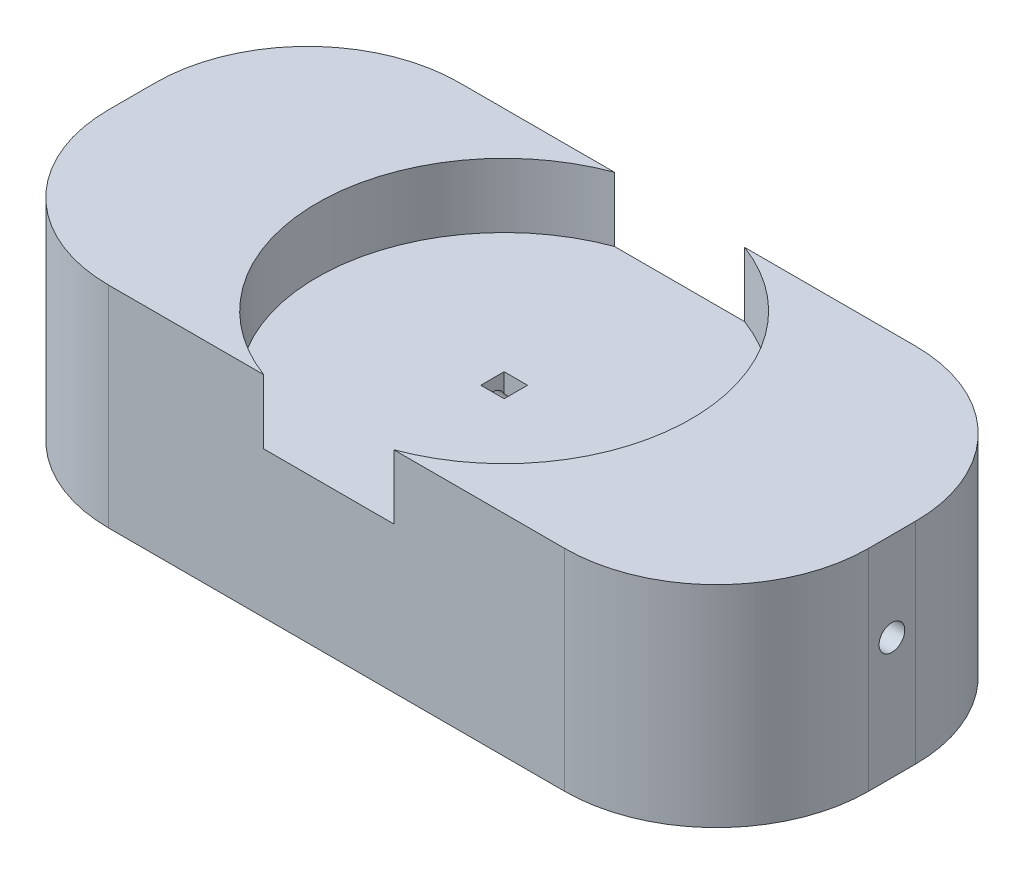
SolidWorks part; units mm, degrees
ref_plane "Front Plane" through (0, 0, 0) normal (0, 0, 1) x (1, 0, 0)
ref_plane "Top Plane" through (0, 0, 0) normal (0, 1, 0) x (1, 0, 0)
ref_plane "Right Plane" through (0, 0, 0) normal (1, 0, 0) x (0, 0, -1)
sketch "Sketch1" plane through (0, 0, 0) normal (0, 1, 0) x (1, 0, 0)
  line L1 (-25, -15) -> (40, -15)
  line L2 (-25, -15) -> (-25, 15)
  line L3 (-25, 15) -> (40, 15)
  line L4 (40, -15) -> (40, 15)
  line L5 (-25, -15) -> (40, 15) construction
  line L6 (-25, 15) -> (40, -15) construction
  point P0 (0, 0)
  dimension "D1" = 30
  dimension "D2" = 65
extrude "Boss-Extrude1" add sketch "Sketch1" along normal blind 58
sketch "Sketch3" plane through (-25, 0, 0) normal (-1, 0, 0) x (0, 0, 1)
  line L0 (-15, 58) -> (15, 58) construction
  circle A0 centre (0, 50.4) radius 1.1
  dimension "D1" = 2.2
  dimension "D2" = 7.6
fillet "Fillet1" radius 13 4 edges at (40, 29, -15) (-25, 29, -15) (40, 29, 15) (-25, 29, 15)
ref_plane "Plane2" through (0, -10, 0) normal (0, -1, 0) x (-1, 0, 0)
sketch "Sketch15" plane through (0, -10, 0) normal (0, -1, 0) x (-1, 0, 0)
  line L1 (-41.9055, 15.8797) -> (41.7906, 15.8797)
  line L2 (-41.9055, 15.8797) -> (-41.9055, -15.8187)
  line L3 (-41.9055, -15.8187) -> (41.7906, -15.8187)
  line L4 (41.7906, 15.8797) -> (41.7906, -15.8187)
extrude "Cut-Extrude7" cut sketch "Sketch15" against normal blind 50
ref_plane "Plane3" through (0, 40, 0) normal (0, -1, 0) x (-1, 0, 0)
ref_plane "Plane4" through (0, 58, 0) normal (0, 1, 0) x (1, 0, 0)
sketch "Sketch18" plane through (0, 58, 0) normal (0, 1, 0) x (1, 0, 0)
  circle A0 centre (6.8285, 0) radius 16
  dimension "D1" = 32
extrude "Cut-Extrude10" cut sketch "Sketch18" against normal blind 5.5
extrude "Cut-Extrude12" cut sketch "Sketch3" against normal through all
ref_plane "Plane5" through (0, 52.5, 0) normal (0, 1, 0) x (1, 0, 0)
sketch "Sketch21" plane through (0, 52.5, 0) normal (0, 1, 0) x (1, 0, 0)
  line L1 (5.8285, -1) -> (7.8285, -1)
  line L2 (5.8285, -1) -> (5.8285, 1)
  line L3 (5.8285, 1) -> (7.8285, 1)
  line L4 (7.8285, -1) -> (7.8285, 1)
  line L5 (5.8285, -1) -> (7.8285, 1) construction
  line L6 (5.8285, 1) -> (7.8285, -1) construction
  point P0 (6.8285, 0)
  dimension "D1" = 2
  dimension "D2" = 2
extrude "Cut-Extrude13" cut sketch "Sketch21" against normal blind 8
